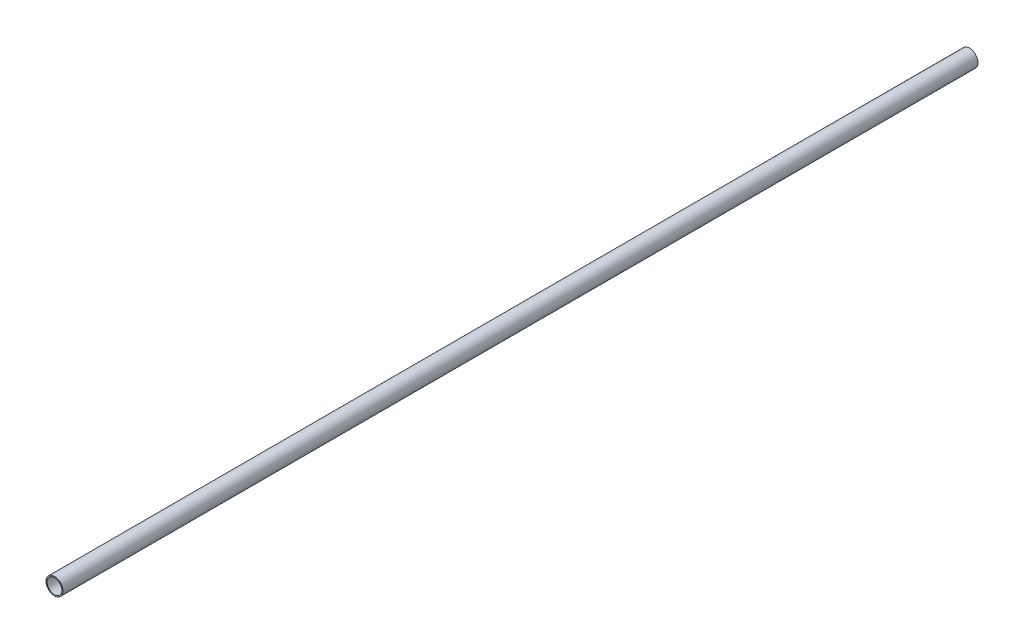
SolidWorks part; units mm, degrees
material "AISI 304"
ref_plane "Front" through (0, 0, 0) normal (0, 0, 1) x (1, 0, 0)
ref_plane "Top" through (0, 0, 0) normal (0, 1, 0) x (1, 0, 0)
ref_plane "Right" through (0, 0, 0) normal (1, 0, 0) x (0, 0, -1)
sketch "Sketch1" plane through (0, 0, 0) normal (0, 0, 1) x (1, 0, 0)
  line L0 (0, 11.049) -> (0, 12.7) construction
  circle A0 centre (0, 0) radius 12.7
  circle A1 centre (0, 0) radius 11.049
  dimension "D1" = 25.4
  dimension "D3" = 1.651
  dimension "D2" = 22.098
extrude "Boss-Extrude1" add sketch "Sketch1" along normal blind 1371.6
